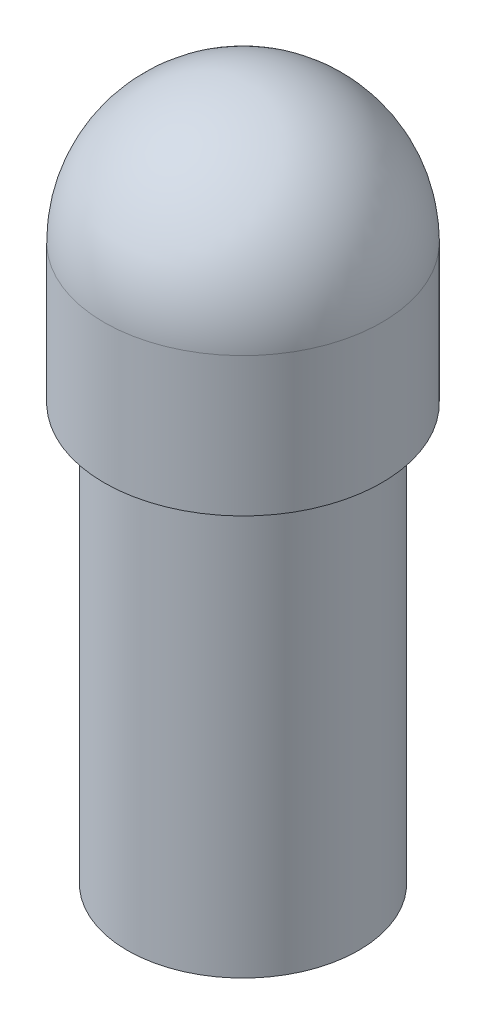
SolidWorks part; units mm, degrees
ref_plane "Front Plane" through (0, 0, 0) normal (0, 0, 1) x (1, 0, 0)
ref_plane "Top Plane" through (0, 0, 0) normal (0, 1, 0) x (1, 0, 0)
ref_plane "Right Plane" through (0, 0, 0) normal (1, 0, 0) x (0, 0, -1)
sketch "Sketch1" plane through (0, 0, 0) normal (0, 1, 0) x (1, 0, 0)
  circle A0 centre (0, 0) radius 5
  dimension "D1" = 10
extrude "Boss-Extrude1" add sketch "Sketch1" along normal blind 18
sketch "Sketch2" plane through (0, 18, 0) normal (0, 1, 0) x (1, 0, 0)
  circle A0 centre (0, 0) radius 6
  dimension "D1" = 12
extrude "Boss-Extrude2" add sketch "Sketch2" along normal blind 12
fillet "Fillet2" radius 6 1 edges at (0, 30, 6)
